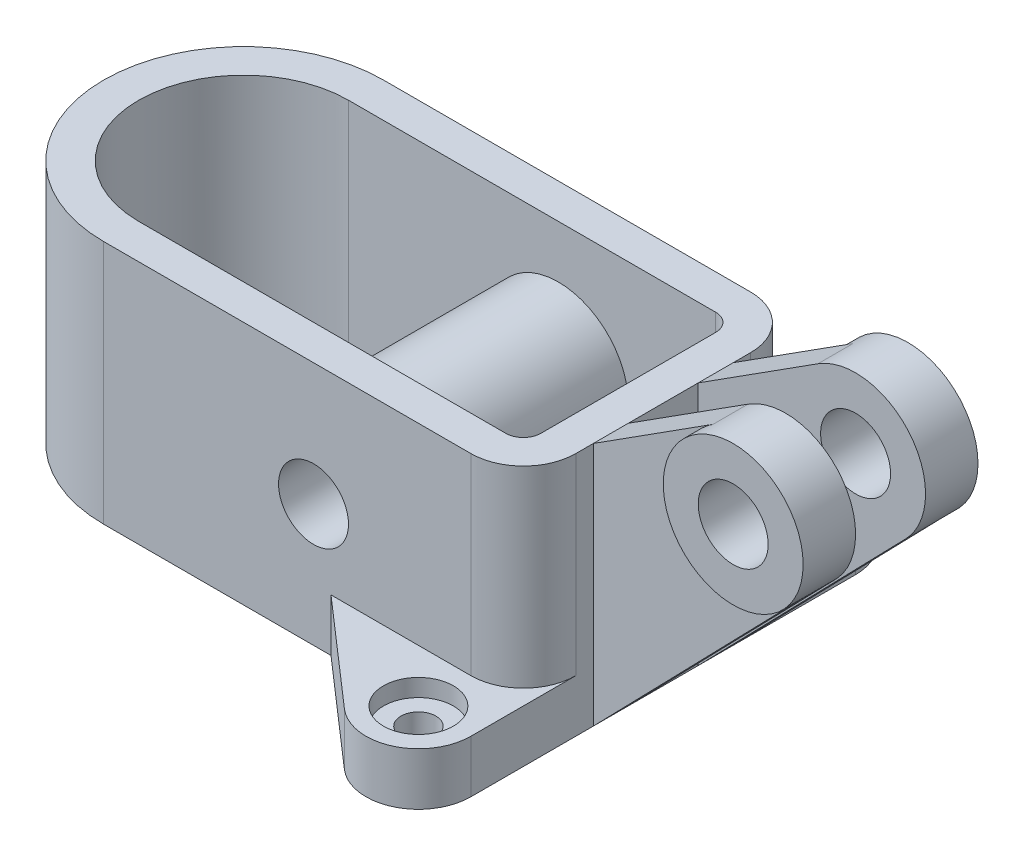
SolidWorks part; units mm, degrees
ref_plane "Front Plane" through (0, 0, 0) normal (0, 0, 1) x (1, 0, 0)
ref_plane "Top Plane" through (0, 0, 0) normal (0, 1, 0) x (1, 0, 0)
ref_plane "Right Plane" through (0, 0, 0) normal (1, 0, 0) x (0, 0, -1)
sketch "Sketch1" plane through (0, 0, 0) normal (0, 1, 0) x (1, 0, 0)
  line L0 (0, 0) -> (-137.7626, 0) construction
  line L1 (0, 40) -> (105, 40)
  line L3 (0, -40) -> (105, -40)
  line L4 (120, 25) -> (120, -25)
  line L5 (0, -30) -> (105, -30)
  line L6 (110, 25) -> (110, -25)
  line L7 (0, 30) -> (105, 30)
  arc A0 (0, 40) -> (0, -40) centre (0, 0) ccw
  arc A1 (105, -40) -> (120, -25) centre (105, -25) ccw
  arc A2 (105, 40) -> (120, 25) centre (105, 25) cw
  arc A3 (0, 30) -> (0, -30) centre (0, 0) ccw
  arc A4 (105, -30) -> (110, -25) centre (105, -25) ccw
  arc A5 (105, 30) -> (110, 25) centre (105, 25) cw
  point P1 (-150.4593, 45.5204)
  point P9 (-45.7031, 0)
  dimension "D1" = 80
  dimension "D3" = 15
  dimension "D2" = 120
  dimension "D4" = 10
extrude "Boss-Extrude1" add sketch "Sketch1" along normal blind 70
sketch "Sketch2" plane through (0, 0, 40) normal (0, 0, 1) x (1, 0, 0)
  line L0 (-40, 35) -> (130.6445, 35) construction
  line L1 (-40, 70) -> (-40, 0) construction
  line L2 (120, 70) -> (120, 0) construction
  circle A0 centre (60, 35) radius 20
  point P6 (0, 0)
  point P9 (0, 0)
  dimension "D1" = 40
  dimension "D2" = 60
extrude "Boss-Extrude2" add sketch "Sketch2" against normal through all
sketch "Sketch3" plane through (0, 0, 0) normal (0, 1, 0) x (1, 0, 0)
  line L0 (120, -25) -> (120, -55)
  line L2 (95.137, -66.3014) -> (65, -40)
  line L3 (0, -40) -> (105, -40) construction
  line L4 (65, -40) -> (105, -40)
  arc A0 (95.137, -66.3014) -> (120, -55) centre (105, -55) ccw
  arc A1 (105, -40) -> (120, -25) centre (105, -25) ccw construction
  arc A2 (105, -40) -> (120, -25) centre (105, -25) ccw
  point P1 (35.7185, -16.0094)
  point P2 (95.8032, -66.3014)
  point P3 (105, -68.1146)
  point P8 (36.3246, -35.9267)
  point P13 (0, 0)
  dimension "D1" = 30
  dimension "D2" = 40
  dimension "D3" = 15
extrude "Boss-Extrude3" add sketch "Sketch3" along normal blind 15
mirror "Mirror1" about plane through (0, 0, 0) normal (0, 0, 1) of "Boss-Extrude3"
hole_wizard "Hole1" positions "Sketch4" profile "Sketch5" legacy end condition up to next
sketch "Sketch4" plane through (0, 15, 0) normal (0, 1, 0) x (1, 0, 0)
  point P0 (105, -55)
  point P3 (105, 55)
sketch "Sketch5" plane through (105, 15, 55) normal (1, 0, 0) x (0, 0, 1)
  line L0 (0, 0) -> (0, 15)
  line L1 (0, 15) -> (5, 15)
  line L2 (5, 15) -> (5, 5)
  line L3 (5, 5) -> (10, 5)
  line L4 (10, 5) -> (10, 0)
  line L5 (10, 0) -> (0, 0)
  line L6 (0, 110) -> (0, -10) construction
  dimension "Diameter" = 10
  dimension "Depth" = 15
  dimension "C-Bore Diameter" = 20
  dimension "C-Bore Depth" = 5
hole_wizard "Hole2" positions "Sketch8" profile "Sketch9" legacy end condition up to next
sketch "Sketch8" plane through (0, 0, 40) normal (0, 0, 1) x (1, 0, 0)
  point P0 (60, 35)
sketch "Sketch9" plane through (60, 35, 40) normal (1, 0, 0) x (0, -1, 0)
  line L0 (0, 0) -> (0, 80)
  line L1 (0, 80) -> (5, 80)
  line L2 (5, 80) -> (5, 20)
  line L3 (5, 20) -> (10, 20)
  line L4 (10, 20) -> (10, 0)
  line L5 (10, 0) -> (0, 0)
  line L6 (0, 110) -> (0, -10) construction
  dimension "Diameter" = 10
  dimension "Depth" = 80
  dimension "C-Bore Diameter" = 20
  dimension "C-Bore Depth" = 20
sketch "Sketch10" plane through (0, 0, 0) normal (0, 0, 1) x (1, 0, 0)
  line L0 (95.137, 0) -> (120, 0) construction
  line L5 (105, 70) -> (105, 15) construction
  circle A0 centre (165, 75) radius 20
  circle A1 centre (165, 75) radius 10
  dimension "D1" = 40
  dimension "D4" = 20
  dimension "D2" = 75
  dimension "D3" = 60
extrude "Boss-Extrude4" add sketch "Sketch10" along normal blind 15 from offset 10 separate body
sketch "Sketch11" plane through (0, 0, 0) normal (0, 0, 1) x (1, 0, 0)
  circle A0 centre (165, 75) radius 10 construction
  circle A1 centre (165, 75) radius 20 construction
  circle A2 centre (165, 75) radius 10
  circle A3 centre (165, 75) radius 20
extrude "Boss-Extrude5" add sketch "Sketch11" against normal blind 15 from offset 10 separate body offset against normal yes
sketch "Sketch12" plane through (0, 0, -10) normal (0, 0, 1) x (1, 0, 0)
  line L0 (120, 15) -> (120, 0) construction
  line L1 (120, 70) -> (120, 15) construction
  line L2 (120, 15) -> (120, 0)
  line L3 (120, 70) -> (120, 15)
  line L4 (120, 70) -> (154.238, 91.8576)
  line L5 (120, 0) -> (179.3425, 61.0611)
  circle A1 centre (165, 75) radius 20
  arc A2 (154.238, 91.8576) -> (179.3425, 61.0611) centre (165, 75) ccw
  dimension "D1" = 0
extrude "Boss-Extrude6" add sketch "Sketch12" against normal blind 10
mirror "Mirror7" about plane through (0, 0, 0) normal (0, 0, 1) of "Boss-Extrude6"
sketch "Sketch13" plane through (0, 0, 0) normal (0, 1, 0) x (1, 0, 0)
  line L0 (-28.2843, 10) -> (0, 10)
  line L1 (0, -10) -> (-28.2843, -10)
  arc A0 (0, -10) -> (0, 10) centre (0, 0) ccw
  arc A1 (0, 30) -> (0, -30) centre (0, 0) ccw construction
  arc A2 (-28.2843, 10) -> (-28.2843, -10) centre (0, 0) ccw
  circle A3 centre (0, 0) radius 5
  dimension "D1" = 20
  dimension "D2" = 10
extrude "Boss-Extrude7" add sketch "Sketch13" along normal blind 15
